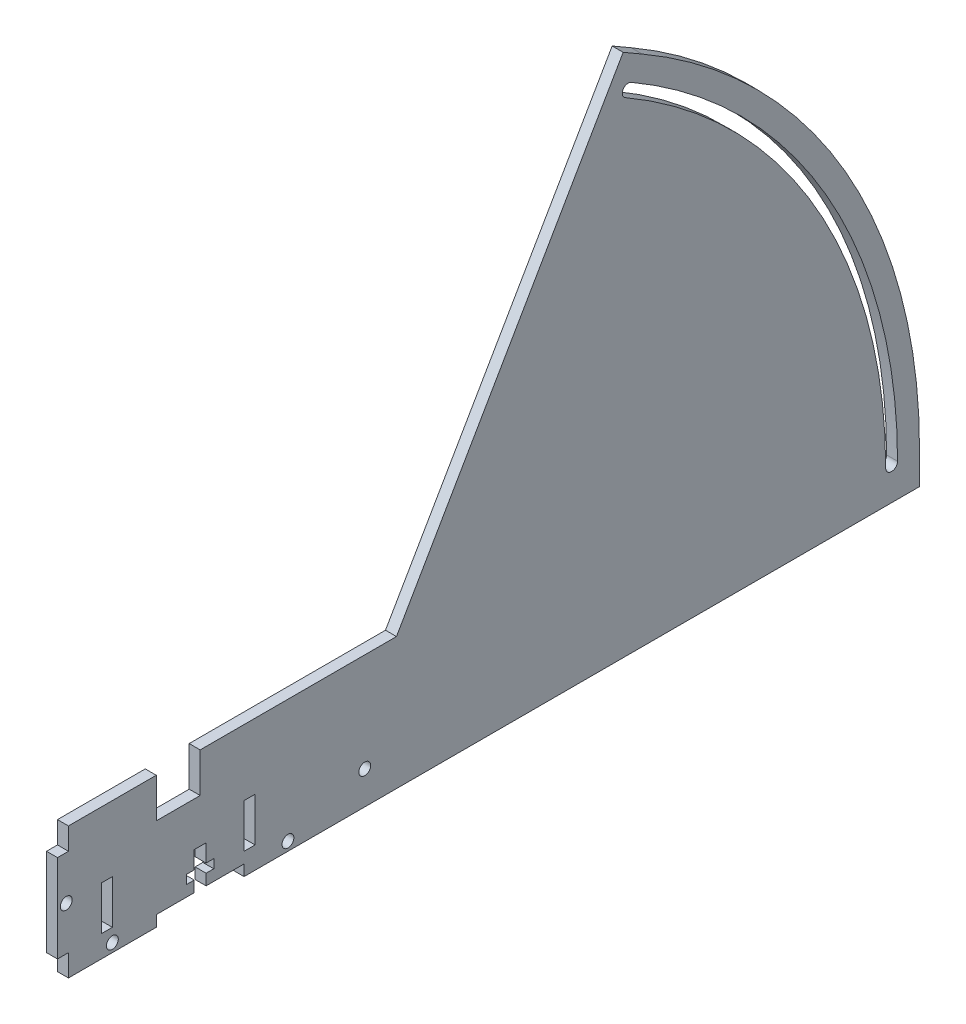
SolidWorks part; units mm, degrees
ref_plane "Front Plane" through (0, 0, 0) normal (0, 0, 1) x (1, 0, 0)
ref_plane "Top Plane" through (0, 0, 0) normal (0, 1, 0) x (1, 0, 0)
ref_plane "Right Plane" through (0, 0, 0) normal (1, 0, 0) x (0, 0, -1)
sketch "Sketch1" plane through (0, 0, 0) normal (1, 0, 0) x (0, 0, -1)
  line L0 (0, 0) -> (160.4645, 0)
  line L1 (80.2322, 148.499) -> (74.733, 151.674)
  line L2 (74.733, 151.674) -> (9.161, 38.1)
  line L3 (-85.725, 38.1) -> (-60.325, 38.1)
  line L4 (-86.36, 19.05) -> (-88.9, 19.05) construction
  line L5 (-88.9, 19.05) -> (13.339, 19.05) construction
  line L6 (-88.9, 31.75) -> (-88.9, 6.35)
  line L7 (-85.725, 0) -> (-60.325, 0)
  line L8 (-88.9, 6.35) -> (-85.725, 6.35)
  line L9 (-85.725, 6.35) -> (-85.725, 0)
  line L10 (-85.725, 31.75) -> (-85.725, 38.1)
  line L11 (-88.9, 31.75) -> (-85.725, 31.75)
  line L12 (-76.2, 19.05) -> (-76.2, 6.35)
  line L13 (-76.2, 6.35) -> (-73.025, 6.35)
  line L14 (-73.025, 6.35) -> (-73.025, 19.05)
  line L15 (-73.025, 19.05) -> (-76.2, 19.05)
  line L16 (-53.975, 38.1) -> (-53.975, -15.875) construction
  line L17 (-34.925, 19.05) -> (-31.75, 19.05)
  line L18 (-34.925, 6.35) -> (-34.925, 19.05)
  line L19 (-31.75, 6.35) -> (-34.925, 6.35)
  line L20 (-31.75, 19.05) -> (-31.75, 6.35)
  line L21 (0, 9.5326) -> (0, 0) construction
  line L22 (0, 0) -> (0.1612, 0.2243) construction
  line L23 (0, 9.5326) -> (152.4, 9.5326) construction
  line L24 (0, 9.5326) -> (76.2, 141.5149) construction
  line L25 (-60.325, 0) -> (-60.325, 3.175)
  line L26 (160.4645, 0) -> (160.4645, 9.5326)
  line L27 (-60.325, 3.175) -> (-49.3395, 3.175)
  line L28 (-34.925, 3.175) -> (-34.925, 0)
  line L29 (-34.925, 0) -> (0, 0)
  line L30 (-47.625, 3.175) -> (-47.625, 14.1937) construction
  line L31 (-49.3395, 3.175) -> (-49.3395, 6.35)
  line L32 (-49.3395, 6.35) -> (-51.562, 6.35)
  line L33 (-51.562, 6.35) -> (-51.562, 8.89)
  line L34 (-51.562, 8.89) -> (-49.3395, 8.89)
  line L35 (-49.3395, 8.89) -> (-49.3395, 13.97)
  line L36 (-49.3395, 13.97) -> (-45.9105, 13.97)
  line L37 (-45.9105, 8.89) -> (-45.9105, 13.97)
  line L38 (-43.688, 8.89) -> (-45.9105, 8.89)
  line L39 (-43.688, 6.35) -> (-43.688, 8.89)
  line L40 (-45.9105, 6.35) -> (-43.688, 6.35)
  line L41 (-45.9105, 3.175) -> (-45.9105, 6.35)
  line L42 (-45.9105, 3.175) -> (-34.925, 3.175)
  line L43 (-73.025, 0) -> (-73.025, 2.54) construction
  line L44 (-22.225, 0) -> (-22.225, 2.54) construction
  line L45 (-60.325, 38.1) -> (-60.325, 26.67)
  line L46 (-60.325, 26.67) -> (-47.625, 26.67)
  line L47 (-47.625, 38.1) -> (-47.625, 26.67)
  line L48 (-47.625, 38.1) -> (9.161, 38.1)
  arc A0 (160.4645, 9.5326) -> (80.2322, 148.499) centre (0, 9.5326) ccw
  arc A1 (76.2, 141.5149) -> (152.4, 9.5326) centre (0, 9.5326) cw construction
  arc A2 (154.1145, 9.5326) -> (77.0572, 142.9997) centre (0, 9.5326) ccw
  arc A3 (150.6855, 9.5326) -> (75.3427, 140.0301) centre (0, 9.5326) ccw
  arc A4 (150.6855, 9.5326) -> (154.1145, 9.5326) centre (152.4, 9.5326) ccw
  arc A5 (77.0572, 142.9997) -> (75.3427, 140.0301) centre (76.2, 141.5149) ccw
  circle A6 centre (-86.36, 19.05) radius 1.7145
  circle A7 centre (0, 9.5326) radius 1.7145
  circle A8 centre (-73.025, 2.54) radius 1.7145
  circle A9 centre (-22.225, 2.54) radius 1.7145
  arc A11 (144.3355, 9.5326) -> (160.4645, 9.5326) centre (152.4, 9.5326) ccw construction
  arc A12 (144.3355, 9.5326) -> (72.1677, 134.5308) centre (0, 9.5326) ccw construction
  arc A13 (80.2322, 148.499) -> (72.1677, 134.5308) centre (76.2, 141.5149) ccw construction
  point P8 (131.9823, 85.7326)
  point P59 (-47.625, 13.97)
  point P74 (-53.975, 26.67)
  dimension "D5" = 9.5326
  dimension "D6" = 9.5326
  dimension "D7" = 3.429
  dimension "D19" = 3.429
  dimension "D16" = 3.429
  dimension "D3" = 38.1
  dimension "D4" = 88.9
  dimension "D8" = 2.54
  dimension "D9" = 3.175
  dimension "D10" = 6.35
  dimension "D11" = 3.175
  dimension "D12" = 12.7
  dimension "D13" = 19.05
  dimension "D14" = 9.525
  dimension "D15" = 19.05
  dimension "D17" = 152.4
  dimension "D18" = 25.4
  dimension "D20" = 6.35
  dimension "D21" = 60
  dimension "D22" = 6.35
  dimension "D23" = 25.4
  dimension "D24" = 3.175
  dimension "D25" = 1.7145
  dimension "D26" = 3.937
  dimension "D27" = 2.54
  dimension "D28" = 13.97
  dimension "D29" = 3.175
  dimension "D30" = 12.7
  dimension "D31" = 6.35
  dimension "D32" = 11.43
extrude "Boss-Extrude2" add sketch "Sketch1" along normal blind 3.175
